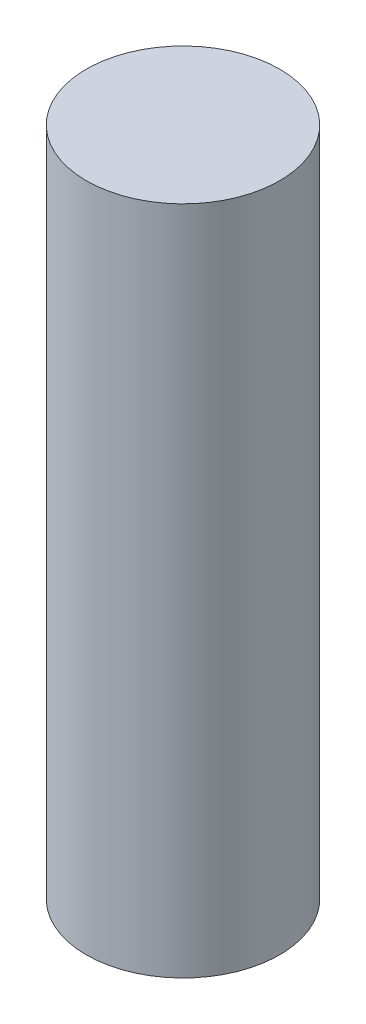
SolidWorks part; units mm, degrees
material "ABS"
ref_plane "Front Plane" through (0, 0, 0) normal (0, 0, 1) x (1, 0, 0)
ref_plane "Top Plane" through (0, 0, 0) normal (0, 1, 0) x (1, 0, 0)
ref_plane "Right Plane" through (0, 0, 0) normal (1, 0, 0) x (0, 0, -1)
sketch "Sketch1" plane through (0, 0, 0) normal (0, 1, 0) x (1, 0, 0)
  circle A0 centre (0, 0) radius 2.8575
  point P3 (0, 2.8575)
  point P4 (2.8575, 0)
  point P5 (0, -2.8575)
  point P6 (-2.8575, 0)
  dimension "D1" = 5.715
extrude "Boss-Extrude1" add sketch "Sketch1" along normal blind 19.812 contours A0
sketch "Sketch2" plane through (0, 19.812, 0) normal (0, 1, 0) x (1, 0, 0)
  circle A0 centre (0, 0) radius 2.8575 construction
  point P0 (0, 2.8575)
  point P1 (2.8575, 0)
  point P4 (0, -2.8575)
  point P5 (-2.8575, 0)
  dimension "D1" = 5.715
  dimension "D2" = 5.715
